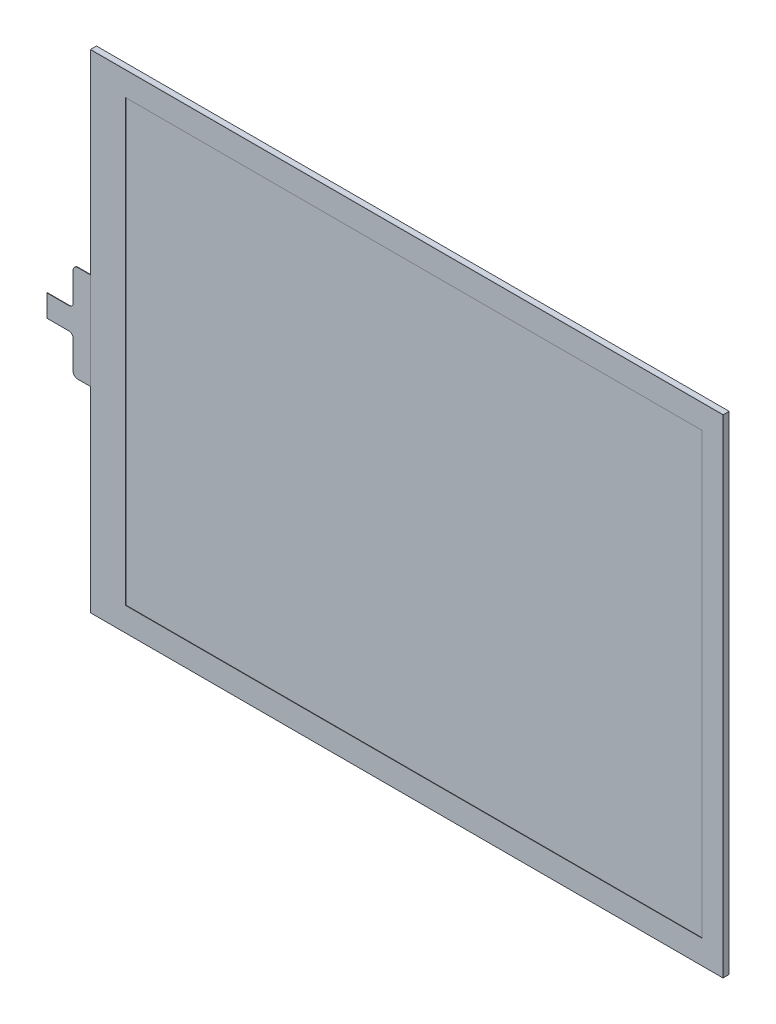
SolidWorks part; units mm, degrees
ref_plane "Front Plane" through (0, 0, 0) normal (0, 0, 1) x (1, 0, 0)
ref_plane "Top Plane" through (0, 0, 0) normal (0, 1, 0) x (1, 0, 0)
ref_plane "Right Plane" through (0, 0, 0) normal (1, 0, 0) x (0, 0, -1)
sketch "Sketch1" plane through (0, 0, 0) normal (0, 0, 1) x (1, 0, 0)
  line L1 (0, 0) -> (144, 0)
  line L2 (0, 0) -> (0, 111)
  line L3 (0, 111) -> (144, 111)
  line L4 (144, 0) -> (144, 111)
  dimension "D1" = 144
  dimension "D2" = 111
extrude "Boss-Extrude1" add sketch "Sketch1" along normal blind 1.3
sketch "Sketch2" plane through (0, 0, 1.3) normal (0, 0, 1) x (1, 0, 0)
  line L0 (0, 111) -> (0, 0) construction
  line L1 (0, 66.5) -> (-3, 66.5)
  line L2 (0, 66.5) -> (0, 44.5)
  line L3 (0, 44.5) -> (-3, 44.5)
  line L4 (-4, 65.5) -> (-4, 59)
  line L5 (0, 66.5) -> (0, 111) construction
  line L6 (0, 44.5) -> (0, 0) construction
  line L7 (-5, 58) -> (-10, 58)
  line L8 (-10, 58) -> (-10, 53)
  line L9 (-10, 53) -> (-5, 53)
  line L10 (-4, 52) -> (-4, 45.5)
  line L11 (-10, 55.5) -> (0, 55.5) construction
  line L12 (144, 111) -> (0, 111) construction
  arc A0 (-3, 44.5) -> (-4, 45.5) centre (-3, 45.5) cw
  arc A1 (-4, 65.5) -> (-3, 66.5) centre (-3, 65.5) cw
  arc A2 (-4, 52) -> (-5, 53) centre (-5, 52) ccw
  arc A3 (-5, 58) -> (-4, 59) centre (-5, 59) ccw
  point P12 (-4, 44.5)
  point P15 (-4, 66.5)
  dimension "D3" = 1
  dimension "D5" = 1
  dimension "D1" = 22
  dimension "D2" = 4
  dimension "D4" = 5
  dimension "D6" = 10
  dimension "D7" = 55.5
extrude "Boss-Extrude2" add sketch "Sketch2" against normal blind 0.1
sketch "Sketch5" plane through (0, 0, 1.3) normal (0, 0, 1) x (1, 0, 0)
  line L0 (144, 111) -> (0, 111) construction
  line L1 (144, 111) -> (0, 111)
  line L2 (144, 0) -> (144, 111) construction
  line L3 (0, 0) -> (144, 0) construction
  line L4 (0, 44.5) -> (0, 0) construction
  line L5 (0, 44.5) -> (0, 66.5) construction
  line L6 (0, 111) -> (0, 66.5) construction
  line L7 (144, 0) -> (144, 111)
  line L8 (0, 0) -> (144, 0)
  line L9 (0, 44.5) -> (0, 0)
  line L10 (0, 44.5) -> (0, 66.5)
  line L11 (0, 111) -> (0, 66.5)
  line L12 (139.2, 105.55) -> (8, 105.55)
  line L13 (8, 105.55) -> (8, 5.45)
  line L16 (8, 5.45) -> (139.2, 5.45)
  line L17 (139.2, 5.45) -> (139.2, 105.55)
  dimension "D1" = 5.45
  dimension "D2" = 4.8
  dimension "D3" = 5.45
  dimension "D4" = 8
extrude "Boss-Extrude3" add sketch "Sketch5" along normal blind 0.1 separate body
